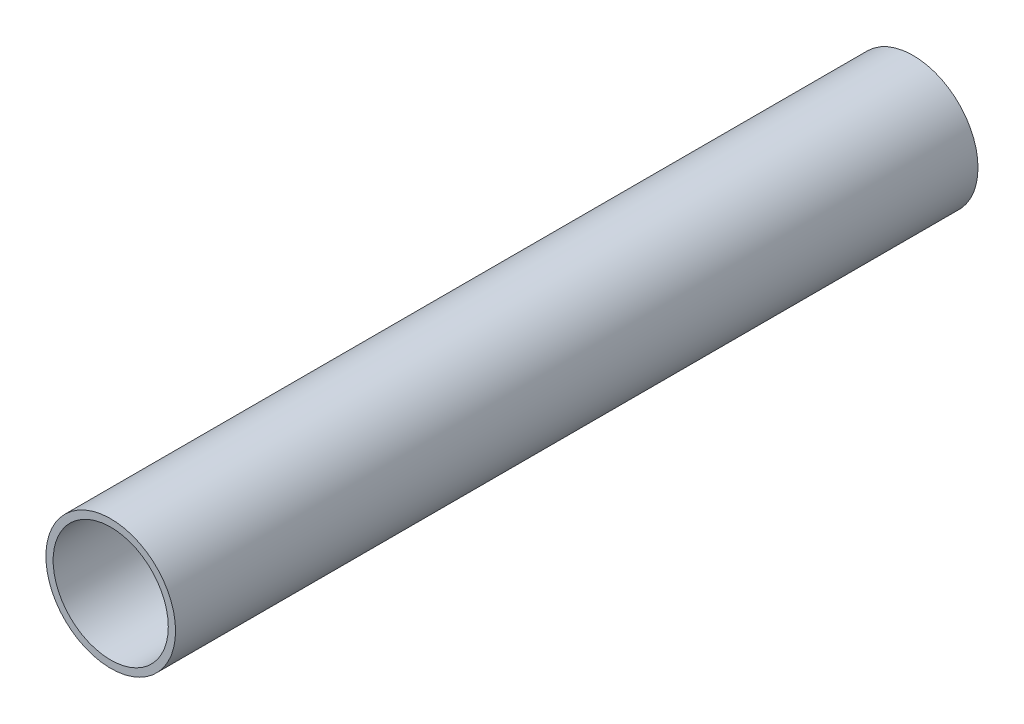
SolidWorks part; units mm, degrees
material "AISI 1020"
ref_plane "Front Plane" through (0, 0, 0) normal (0, 0, 1) x (1, 0, 0)
ref_plane "Top Plane" through (0, 0, 0) normal (0, 1, 0) x (1, 0, 0)
ref_plane "Right Plane" through (0, 0, 0) normal (1, 0, 0) x (0, 0, -1)
sketch "Sketch1" plane through (0, 0, 0) normal (0, 0, 1) x (1, 0, 0)
  circle A0 centre (0.5694, -0.7118) radius 7.0485
  circle A1 centre (0.5694, -0.7118) radius 7.9375
  dimension "D1" = 14.097
  dimension "D2" = 15.875
extrude "Boss-Extrude1" add sketch "Sketch1" along normal blind 98.24
